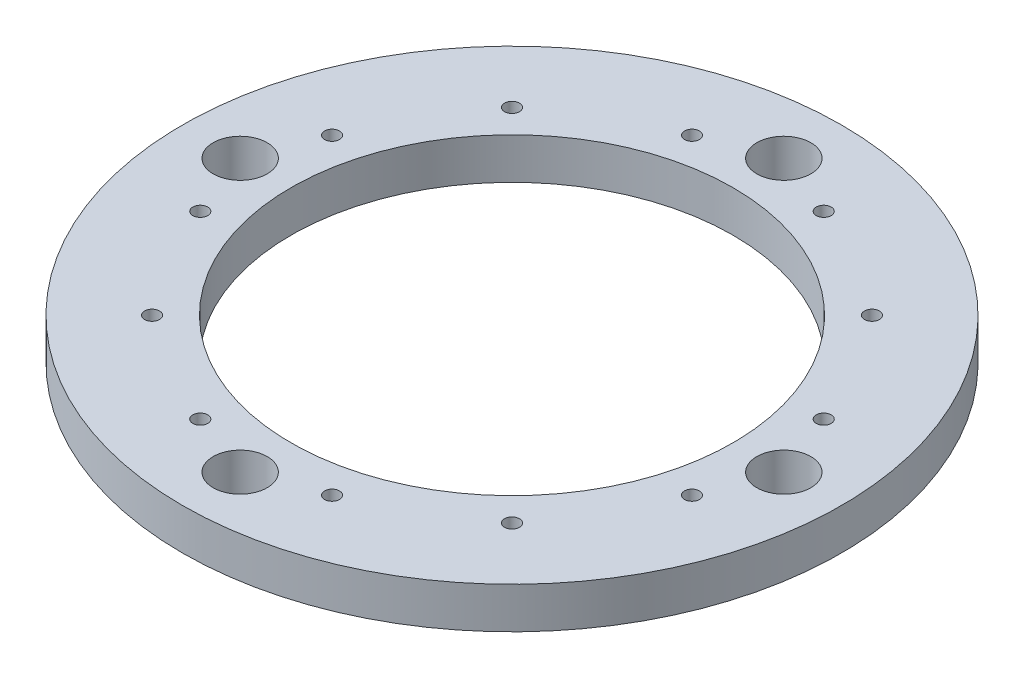
SolidWorks part; units mm, degrees
material "6061 Alloy"
ref_plane "Front Plane" through (0, 0, 0) normal (0, 0, 1) x (1, 0, 0)
ref_plane "Top Plane" through (0, 0, 0) normal (0, 1, 0) x (1, 0, 0)
ref_plane "Right Plane" through (0, 0, 0) normal (1, 0, 0) x (0, 0, -1)
sketch "Sketch1" plane through (0, 0, 0) normal (0, 1, 0) x (1, 0, 0)
  circle A0 centre (0, 0) radius 51.1048
  circle A1 centre (0, 0) radius 76.2
  dimension "D1" = 102.2096
  dimension "D2" = 152.4
extrude "Boss-Extrude1" add sketch "Sketch1" along normal blind 9.525
sketch "Sketch2" plane through (0, 9.525, 0) normal (0, 1, 0) x (1, 0, 0)
  line L0 (-15.2315, 56.8447) -> (0, 0) construction
  line L1 (0, 0) -> (0, 76.2) construction
  circle A0 centre (-15.2315, 56.8447) radius 1.7272
  circle A1 centre (0, 0) radius 76.2 construction
  circle A2 centre (15.2315, 56.8447) radius 1.7272
  circle A3 centre (41.6132, 41.6132) radius 1.7272
  circle A4 centre (56.8447, 15.2315) radius 1.7272
  circle A5 centre (56.8447, -15.2315) radius 1.7272
  circle A6 centre (41.6132, -41.6132) radius 1.7272
  circle A7 centre (15.2315, -56.8447) radius 1.7272
  circle A8 centre (-15.2315, -56.8447) radius 1.7272
  circle A9 centre (-41.6132, -41.6132) radius 1.7272
  circle A10 centre (-56.8447, -15.2315) radius 1.7272
  circle A11 centre (-56.8447, 15.2315) radius 1.7272
  circle A12 centre (-41.6132, 41.6132) radius 1.7272
  point P33 (0, 0)
  dimension "D1" = 15
  dimension "D2" = 3.4544
  dimension "D3" = 58.85
  dimension "D4" = 12
extrude "Cut-Extrude1" cut sketch "Sketch2" against normal through all
sketch "Sketch3" plane through (0, 9.525, 0) normal (0, 1, 0) x (1, 0, 0)
  line L0 (-62.85, 0) -> (0, 0) construction
  circle A0 centre (-62.85, 0) radius 6.25
  circle A1 centre (0, 62.85) radius 6.25
  circle A2 centre (62.85, 0) radius 6.25
  circle A3 centre (0, -62.85) radius 6.25
  point P13 (0, 0)
  dimension "D1" = 12.5
  dimension "D2" = 62.85
  dimension "D3" = 4
extrude "Cut-Extrude2" cut sketch "Sketch3" against normal through all
equation "\"Ring Thickness\"= 0.375"
equation "\"Outer Diameter\"= 6"
equation "\"Inner Diameter\"= 4.024"
equation "\"D1@Sketch1\"=\"Inner Diameter\""
equation "\"D2@Sketch1\"=\"Outer Diameter\""
equation "\"D1@Boss-Extrude1\"=\"Ring Thickness\""
